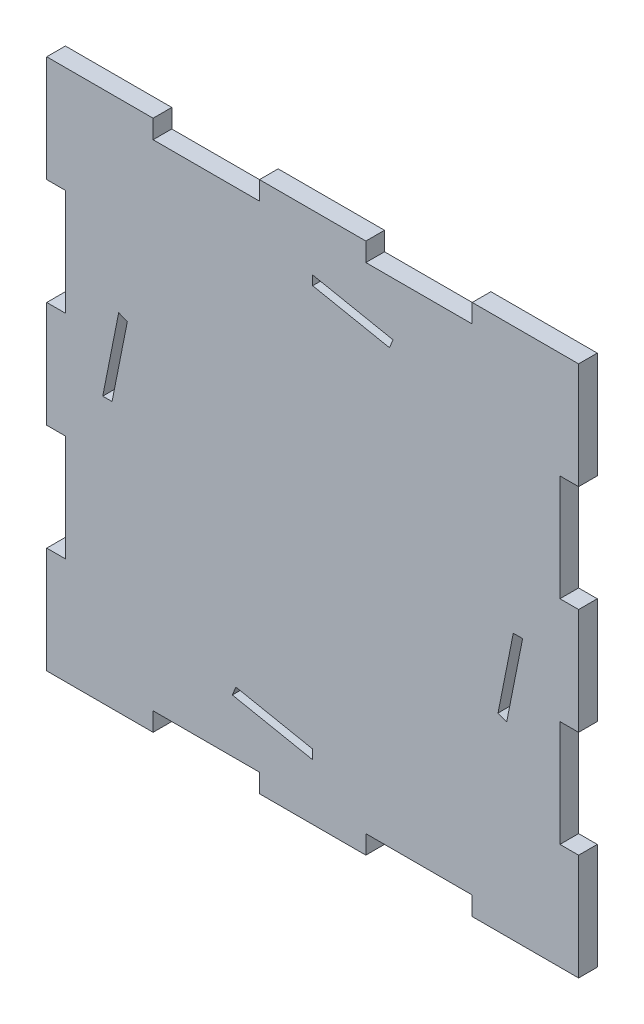
SolidWorks part; units mm, degrees
ref_plane "Front Plane" through (0, 0, 0) normal (0, 0, 1) x (1, 0, 0)
ref_plane "Top Plane" through (0, 0, 0) normal (0, 1, 0) x (1, 0, 0)
ref_plane "Right Plane" through (0, 0, 0) normal (1, 0, 0) x (0, 0, -1)
sketch "Sketch1" plane through (0, 0, 0) normal (0, 0, 1) x (1, 0, 0)
  line L1 (0, 0) -> (144.78, 0)
  line L2 (0, 0) -> (0, 144.78)
  line L3 (0, 144.78) -> (144.78, 144.78)
  line L4 (144.78, 0) -> (144.78, 144.78)
  dimension "D1" = 144.78
  dimension "D2" = 144.78
extrude "Boss-Extrude1" add sketch "Sketch1" along normal blind 5.08 contours L3 L4 L1 L2
sketch "Sketch3" plane through (0, 0, 5.08) normal (0, 0, 1) x (1, 0, 0)
  line L0 (0, 0) -> (0, 144.78) construction
  line L1 (0, 115.824) -> (5.08, 115.824)
  line L2 (0, 115.824) -> (0, 86.868)
  line L3 (0, 86.868) -> (5.08, 86.868)
  line L4 (5.08, 115.824) -> (5.08, 86.868)
  line L5 (144.78, 0) -> (144.78, 144.78) construction
  line L6 (0, 57.912) -> (5.08, 57.912)
  line L7 (0, 57.912) -> (0, 28.956)
  line L8 (0, 28.956) -> (5.08, 28.956)
  line L9 (5.08, 57.912) -> (5.08, 28.956)
  line L10 (144.78, 115.824) -> (139.7, 115.824)
  line L11 (144.78, 115.824) -> (144.78, 86.868)
  line L12 (144.78, 86.868) -> (139.7, 86.868)
  line L13 (139.7, 115.824) -> (139.7, 86.868)
  line L14 (5.08, 115.824) -> (5.08, 144.78) construction
  line L15 (144.78, 57.912) -> (139.7, 57.912)
  line L16 (144.78, 57.912) -> (144.78, 28.956)
  line L17 (144.78, 28.956) -> (139.7, 28.956)
  line L18 (139.7, 57.912) -> (139.7, 28.956)
  line L19 (0, 144.78) -> (144.78, 144.78) construction
  line L20 (5.08, 86.868) -> (5.08, 57.912) construction
  line L21 (5.08, 28.956) -> (5.08, 0) construction
  line L22 (0, 0) -> (144.78, 0) construction
  line L23 (139.7, 115.824) -> (139.7, 144.78) construction
  line L24 (139.7, 86.868) -> (139.7, 57.912) construction
  line L25 (139.7, 28.956) -> (139.7, 0) construction
  line L26 (28.956, 139.7) -> (0, 139.7) construction
  line L27 (28.956, 144.78) -> (57.912, 144.78)
  line L28 (28.956, 144.78) -> (28.956, 139.7)
  line L29 (28.956, 139.7) -> (57.912, 139.7)
  line L30 (57.912, 144.78) -> (57.912, 139.7)
  line L31 (86.868, 144.78) -> (115.824, 144.78)
  line L32 (86.868, 144.78) -> (86.868, 139.7)
  line L33 (86.868, 139.7) -> (115.824, 139.7)
  line L34 (115.824, 144.78) -> (115.824, 139.7)
  line L35 (28.956, 0) -> (57.912, 0)
  line L36 (28.956, 0) -> (28.956, 5.08)
  line L37 (28.956, 5.08) -> (57.912, 5.08)
  line L38 (57.912, 0) -> (57.912, 5.08)
  line L39 (86.868, 0) -> (115.824, 0)
  line L40 (86.868, 0) -> (86.868, 5.08)
  line L41 (86.868, 5.08) -> (115.824, 5.08)
  line L42 (115.824, 0) -> (115.824, 5.08)
  line L43 (57.912, 139.7) -> (86.868, 139.7) construction
  line L44 (115.824, 139.7) -> (144.78, 139.7) construction
  line L45 (28.956, 5.08) -> (0, 5.08) construction
  line L46 (57.912, 5.08) -> (86.868, 5.08) construction
  line L47 (115.824, 5.08) -> (144.78, 5.08) construction
  dimension "D1" = 5.08
  dimension "D2" = 5.08
  dimension "D3" = 5.08
  dimension "D4" = 5.08
extrude "Cut-Extrude1" cut sketch "Sketch3" against normal through all
sketch "Sketch7" plane through (0, 0, 5.08) normal (0, 0, 1) x (1, 0, 0)
  line L0 (0, 72.39) -> (144.78, 72.39) construction
  line L3 (0, 57.912) -> (0, 86.868) construction
  line L6 (144.78, 57.912) -> (144.78, 86.868) construction
  line L7 (72.39, 144.78) -> (72.39, 0) construction
  line L8 (57.912, 144.78) -> (86.868, 144.78) construction
  line L9 (57.912, 0) -> (86.868, 0) construction
  line L11 (72.39, 129.54) -> (50.5196, 125.1897) construction
  line L12 (50.5196, 125.1897) -> (31.9788, 112.8012) construction
  line L13 (31.9788, 112.8012) -> (19.5903, 94.2604) construction
  line L14 (19.5903, 94.2604) -> (15.24, 72.39) construction
  line L15 (15.24, 72.39) -> (19.5903, 50.5196) construction
  line L16 (19.5903, 50.5196) -> (31.9788, 31.9788) construction
  line L17 (31.9788, 31.9788) -> (50.5196, 19.5903) construction
  line L18 (50.5196, 19.5903) -> (72.39, 15.24) construction
  line L19 (72.39, 15.24) -> (94.2604, 19.5903) construction
  line L20 (94.2604, 19.5903) -> (112.8012, 31.9788) construction
  line L21 (112.8012, 31.9788) -> (125.1897, 50.5196) construction
  line L22 (125.1897, 50.5196) -> (129.54, 72.39) construction
  line L23 (129.54, 72.39) -> (125.1897, 94.2604) construction
  line L24 (125.1897, 94.2604) -> (112.8012, 112.8012) construction
  line L25 (112.8012, 112.8012) -> (94.2604, 125.1897) construction
  line L26 (94.2604, 125.1897) -> (72.39, 129.54) construction
  line L28 (72.39, 127) -> (51.4917, 122.8431) construction
  line L29 (51.4917, 122.8431) -> (33.7749, 111.0051) construction
  line L30 (33.7749, 111.0051) -> (21.9369, 93.2883) construction
  line L31 (21.9369, 93.2883) -> (17.78, 72.39) construction
  line L32 (17.78, 72.39) -> (21.9369, 51.4917) construction
  line L33 (21.9369, 51.4917) -> (33.7749, 33.7749) construction
  line L34 (33.7749, 33.7749) -> (51.4917, 21.9369) construction
  line L35 (51.4917, 21.9369) -> (72.39, 17.78) construction
  line L36 (72.39, 17.78) -> (93.2883, 21.9369) construction
  line L37 (93.2883, 21.9369) -> (111.0051, 33.7749) construction
  line L38 (111.0051, 33.7749) -> (122.8431, 51.4917) construction
  line L39 (122.8431, 51.4917) -> (127, 72.39) construction
  line L40 (127, 72.39) -> (122.8431, 93.2883) construction
  line L41 (122.8431, 93.2883) -> (111.0051, 111.0051) construction
  line L42 (111.0051, 111.0051) -> (93.2883, 122.8431) construction
  line L43 (93.2883, 122.8431) -> (72.39, 127) construction
  line L44 (72.39, 129.54) -> (94.2604, 125.1897)
  line L45 (94.2604, 125.1897) -> (93.2883, 122.8431)
  line L46 (93.2883, 122.8431) -> (72.39, 127)
  line L47 (72.39, 127) -> (72.39, 129.54)
  line L49 (129.54, 72.39) -> (125.1897, 50.5196)
  line L50 (127, 72.39) -> (122.8431, 51.4917)
  line L51 (122.8431, 51.4917) -> (125.1897, 50.5196)
  line L53 (127, 72.39) -> (129.54, 72.39)
  line L55 (72.39, 15.24) -> (50.5196, 19.5903)
  line L57 (72.39, 17.78) -> (51.4917, 21.9369)
  line L58 (51.4917, 21.9369) -> (50.5196, 19.5903)
  line L60 (72.39, 15.24) -> (72.39, 17.78)
  line L62 (17.78, 72.39) -> (21.9369, 93.2883)
  line L64 (15.24, 72.39) -> (19.5903, 94.2604)
  line L65 (19.5903, 94.2604) -> (21.9369, 93.2883)
  line L67 (15.24, 72.39) -> (17.78, 72.39)
  circle A0 centre (72.39, 72.39) radius 56.0519 construction
  circle A1 centre (72.39, 72.39) radius 53.5607 construction
  dimension "D1" = 114.3
  dimension "D2" = 2.54
extrude "Cut-Extrude3" cut sketch "Sketch7" against normal through all contours L57 L58 L55 L60 | L50 L51 L49 L53 | L46 L47 L44 L45 | L62 L65 L64 L67
equation "\"MDF\"= .2"
equation "\"Foamcore\"= .1"
equation "\"GMaterial\"= \"MDF\""
equation "\"CutDistance\" = .1"
equation "\"D1@Boss-Extrude1\"=\"GMaterial\""
equation "\"D1@Sketch1\"=\"GMaterial\"+5.5"
equation "\"D2@Sketch1\"=\"GMaterial\"  + 5.5"
equation "\"D1@Sketch3\"=\"GMaterial\""
equation "\"D2@Sketch3\"=\"GMaterial\""
equation "\"D3@Sketch3\"=\"GMaterial\""
equation "\"D4@Sketch3\"=\"GMaterial\""
equation "\"D2@Sketch7\"=\"Foamcore\""
